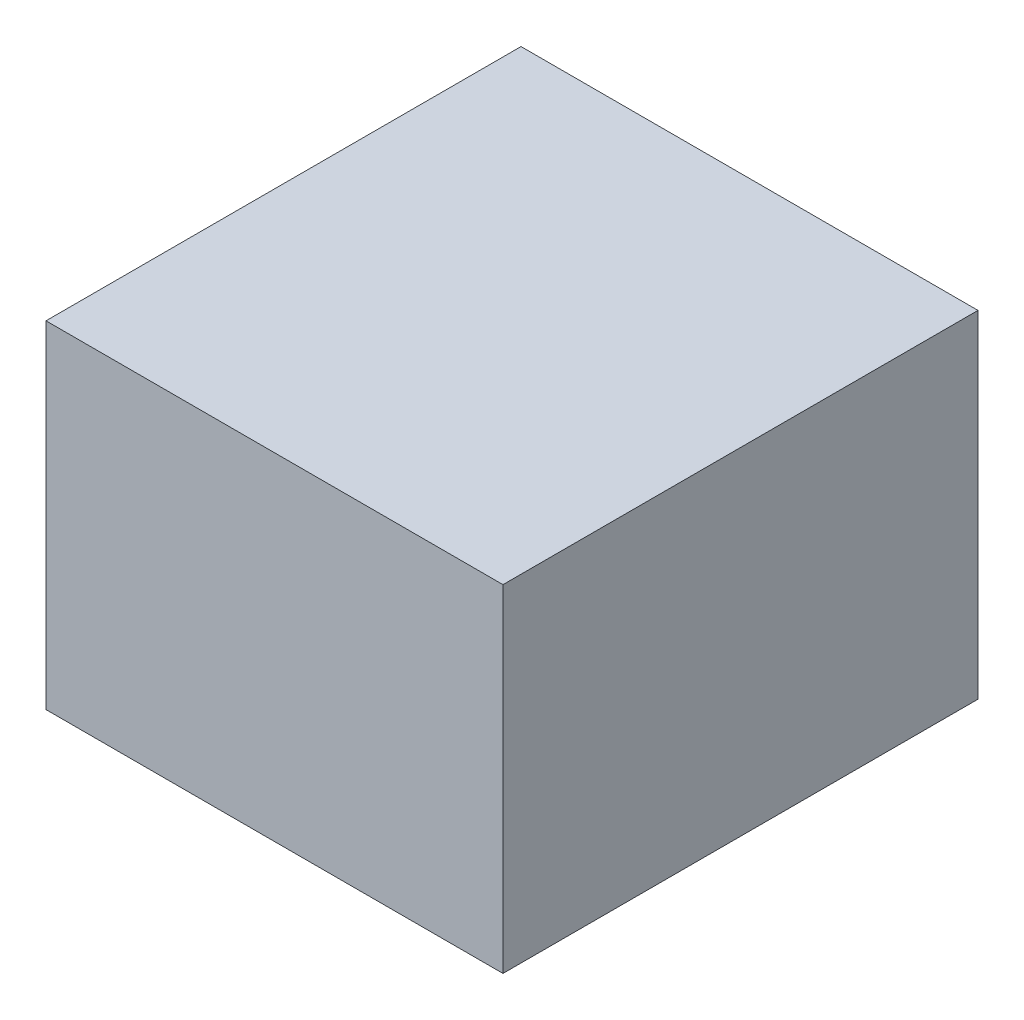
SolidWorks part; units mm, degrees
ref_plane "Front Plane" through (0, 0, 0) normal (0, 0, 1) x (1, 0, 0)
ref_plane "Top Plane" through (0, 0, 0) normal (0, 1, 0) x (1, 0, 0)
ref_plane "Right Plane" through (0, 0, 0) normal (1, 0, 0) x (0, 0, -1)
sketch "Sketch1" plane through (0, 0, 0) normal (0, 1, 0) x (1, 0, 0)
  line L1 (-3.8, -3.95) -> (3.8, -3.95)
  line L2 (-3.8, -3.95) -> (-3.8, 3.95)
  line L3 (-3.8, 3.95) -> (3.8, 3.95)
  line L4 (3.8, -3.95) -> (3.8, 3.95)
  line L5 (-3.8, -3.95) -> (3.8, 3.95) construction
  line L6 (-3.8, 3.95) -> (3.8, -3.95) construction
  point P0 (0, 0)
  dimension "D1" = 7.6
  dimension "D2" = 7.9
extrude "Boss-Extrude1" add sketch "Sketch1" along normal blind 5.6
sketch "Sketch3" plane through (-3.8, 0, 0) normal (-1, 0, 0) x (0, 0, 1)
  line L1 (-2.35, 4.8) -> (2.35, 4.8)
  line L2 (-2.35, 4.8) -> (-2.35, 0.8)
  line L3 (-2.35, 0.8) -> (2.35, 0.8)
  line L4 (2.35, 4.8) -> (2.35, 0.8)
  line L5 (8.7425, 2.8) -> (-8.9499, 2.8) construction
  line L6 (0, 7.9922) -> (0, -4.0274) construction
  line L7 (-3.95, 5.6) -> (3.95, 5.6) construction
  line L8 (-3.95, 5.6) -> (-3.95, 0) construction
  point P4 (2.35, 2.8)
  point P14 (0, 5.6)
  point P15 (0, 4.8)
  point P18 (-3.95, 2.8)
  dimension "D1" = 4.7
  dimension "D2" = 4
extrude "Cut-Extrude1" cut sketch "Sketch3" against normal blind 4.5
